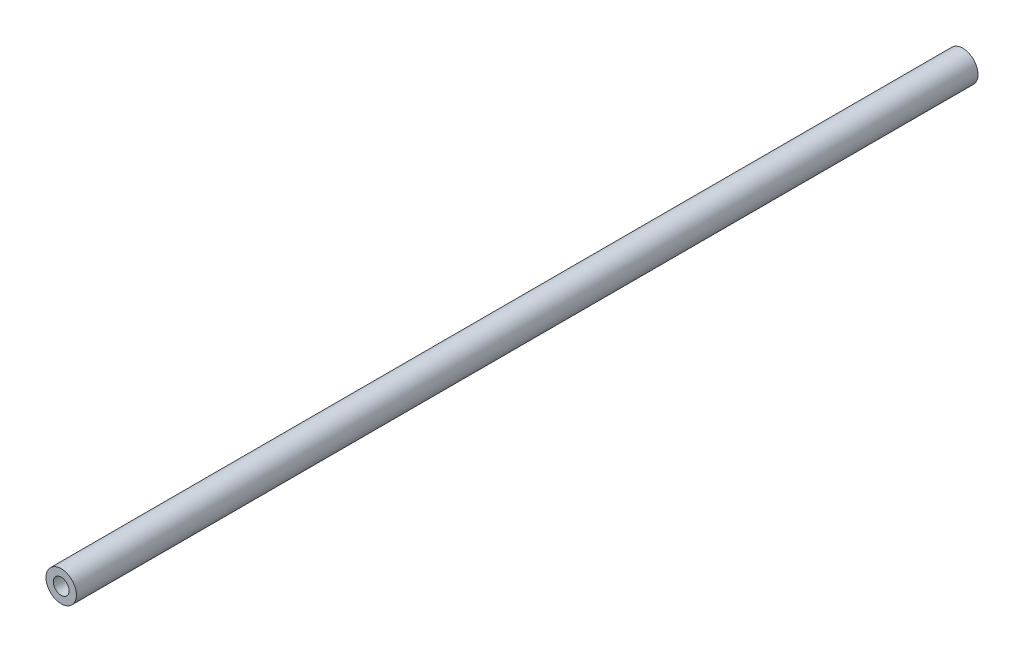
SolidWorks part; units mm, degrees
ref_plane "Front Plane" through (0, 0, 0) normal (0, 0, 1) x (1, 0, 0)
ref_plane "Top Plane" through (0, 0, 0) normal (0, 1, 0) x (1, 0, 0)
ref_plane "Right Plane" through (0, 0, 0) normal (1, 0, 0) x (0, 0, -1)
sketch "Sketch1" plane through (0, 0, 0) normal (0, 0, 1) x (1, 0, 0)
  circle A0 centre (0, 0) radius 0.1714
  circle A1 centre (0, 0) radius 0.0889
  dimension "D1" = 0.3429
  dimension "D2" = 0.1778
extrude "Boss-Extrude1" add sketch "Sketch1" along normal blind 10.16
